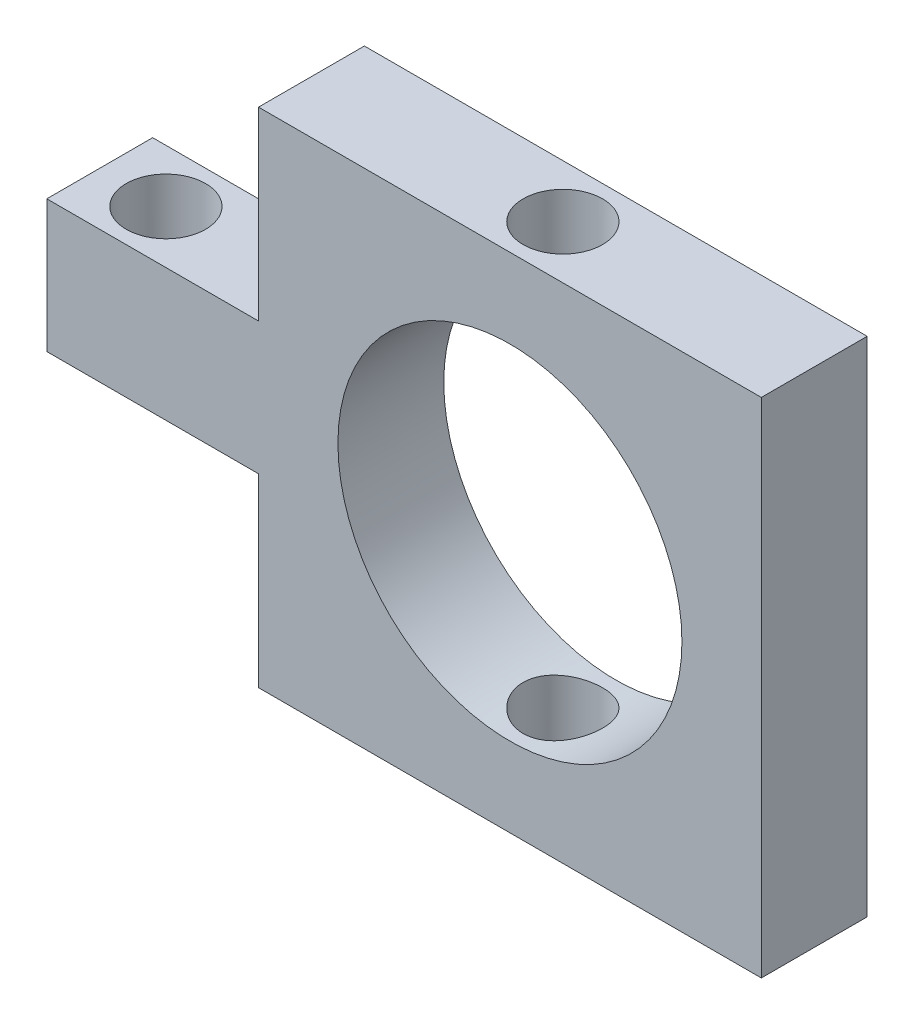
SolidWorks part; units mm, degrees
ref_plane "Front Plane" through (0, 0, 0) normal (0, 0, 1) x (1, 0, 0)
ref_plane "Top Plane" through (0, 0, 0) normal (0, 1, 0) x (1, 0, 0)
ref_plane "Right Plane" through (0, 0, 0) normal (1, 0, 0) x (0, 0, -1)
sketch "Sketch1" plane through (0, 0, 0) normal (0, 0, 1) x (1, 0, 0)
  line L1 (-9.5, -9.5) -> (9.5, -9.5)
  line L2 (-9.5, -9.5) -> (-9.5, 9.5)
  line L3 (-9.5, 9.5) -> (9.5, 9.5)
  line L4 (9.5, -9.5) -> (9.5, 9.5)
  line L5 (-9.5, -9.5) -> (9.5, 9.5) construction
  line L6 (-9.5, 9.5) -> (9.5, -9.5) construction
  circle A2 centre (0, 0) radius 6.5
  dimension "D1" = 13
  dimension "D2" = 19
  dimension "D3" = 19
extrude "Boss-Extrude1" add sketch "Sketch1" along normal blind 4
sketch "Sketch2" plane through (0, 0, 0) normal (0, 1, 0) x (1, 0, 0)
  line L0 (0, -2.2) -> (0, 2.2) construction
  line L2 (9.5, -4) -> (-9.5, -4) construction
  circle A0 centre (0, -2) radius 1.5
  dimension "D1" = 3
  dimension "D2" = 2
extrude "Cut-Extrude1" cut sketch "Sketch2" along normal up to next and the other way up to next
sketch "Sketch5" plane through (-9.5, 0, 0) normal (-1, 0, 0) x (0, 0, 1)
  line L0 (0, -2.5) -> (4, -2.5)
  line L1 (0, -2.5) -> (0, 2.5)
  line L2 (4, -2.5) -> (4, 2.5)
  line L3 (0, 2.5) -> (4, 2.5)
  line L4 (0, -10.45) -> (0, 10.45) construction
  line L5 (4, 9.5) -> (4, -9.5) construction
  line L6 (2.2, 0) -> (-2.2, 0) construction
  dimension "D1" = 2.5
  dimension "D2" = 2.5
extrude "Boss-Extrude3" add sketch "Sketch5" along normal blind 8
sketch "Sketch7" plane through (0, 0, 0) normal (0, 1, 0) x (1, 0, 0)
  line L0 (-17.5, -4) -> (-17.5, 0) construction
  line L1 (-17.5, -4) -> (-9.5, -4) construction
  circle A0 centre (-15, -2) radius 1.5
  dimension "D1" = 3
  dimension "D2" = 2.5
  dimension "D3" = 2
extrude "Cut-Extrude2" cut sketch "Sketch7" against normal up to next and the other way up to next
